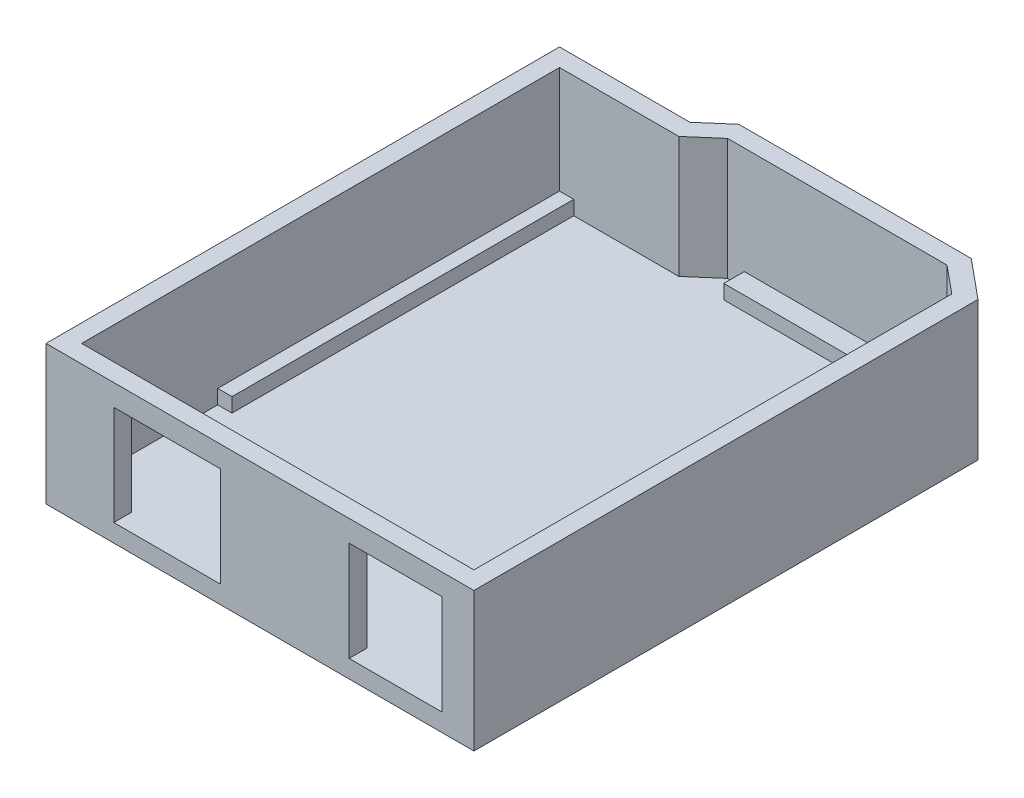
SolidWorks part; units mm, degrees
ref_plane "Front Plane" through (0, 0, 0) normal (0, 0, 1) x (1, 0, 0)
ref_plane "Top Plane" through (0, 0, 0) normal (0, 1, 0) x (1, 0, 0)
ref_plane "Right Plane" through (0, 0, 0) normal (1, 0, 0) x (0, 0, -1)
sketch "Sketch1" plane through (0, 0, 0) normal (0, 1, 0) x (1, 0, 0)
  line L0 (0, 0) -> (0, 67)
  line L1 (0, 67) -> (16.7293, 67)
  line L2 (16.7293, 67) -> (20.3928, 70.1768)
  line L3 (20.3928, 70.1768) -> (51.1578, 70.1768)
  line L4 (0, 0) -> (55, 0)
  line L5 (55, 0) -> (55, 67)
  line L6 (55, 67) -> (51.1578, 70.1768)
  point P8 (51.1578, 70.1768)
  dimension "D1" = 67
  dimension "D2" = 55
extrude "Boss-Extrude1" add sketch "Sketch1" along normal blind 17
shell "Shell1" thickness 2.5
sketch "Sketch2" plane through (0, 0, 0) normal (0, 0, -1) x (-1, 0, 0)
  line L0 (2.5, 17) -> (2.5, -2.5) construction
  line L1 (-22, 14) -> (-7, 14)
  line L2 (-22, 14) -> (-22, 0)
  line L3 (-22, 0) -> (-7, 0)
  line L4 (-7, 14) -> (-7, 0)
  line L10 (-57.5, 17) -> (-57.5, -2.5) construction
  line L11 (-40, 14) -> (-53, 14)
  line L12 (-40, 14) -> (-40, 0)
  line L13 (-40, 0) -> (-53, 0)
  line L14 (-53, 14) -> (-53, 0)
  dimension "D1" = 15
  dimension "D2" = 14
  dimension "D3" = 9.5
  dimension "D4" = 4.5
  dimension "D5" = 13
extrude "Cut-Extrude1" cut sketch "Sketch2" against normal blind 4
sketch "Sketch3" plane through (0, 0, 0) normal (0, 1, 0) x (1, 0, 0)
  line L0 (0, 67) -> (0, 0) construction
  line L1 (0, 69.0781) -> (2, 69.0781)
  line L2 (0, 69.0781) -> (0, 19.0781)
  line L3 (0, 19.0781) -> (2, 19.0781)
  line L4 (2, 69.0781) -> (2, 19.0781)
  line L5 (27.5, 0) -> (27.5, -11.7567) construction
  line L6 (0, 0) -> (55, 0) construction
  line L7 (55, 69.0781) -> (53, 69.0781)
  line L8 (55, 19.0781) -> (53, 19.0781)
  line L9 (53, 69.0781) -> (53, 19.0781)
  line L10 (55, 69.0781) -> (55, 19.0781)
  dimension "D1" = 2
  dimension "D2" = 50
extrude "Boss-Extrude2" add sketch "Sketch3" along normal blind 2
sketch "Sketch4" plane through (0, 0, 0) normal (0, 1, 0) x (1, 0, 0)
  line L1 (22.7348, 67.3021) -> (48.8818, 67.3021)
  line L2 (22.7348, 67.3021) -> (22.7348, 70.1768)
  line L3 (22.7348, 70.1768) -> (48.8818, 70.1768)
  line L4 (48.8818, 67.3021) -> (48.8818, 70.1768)
  line L5 (51.1578, 70.1768) -> (20.3928, 70.1768) construction
  point P4 (22.7348, 74.0146)
  point P5 (48.4343, 66.3431)
  point P6 (23.0544, 74.4621)
  point P7 (48.3704, 70.1768)
  point P10 (48.8818, 67.3021)
extrude "Boss-Extrude3" add sketch "Sketch4" along normal blind 2
